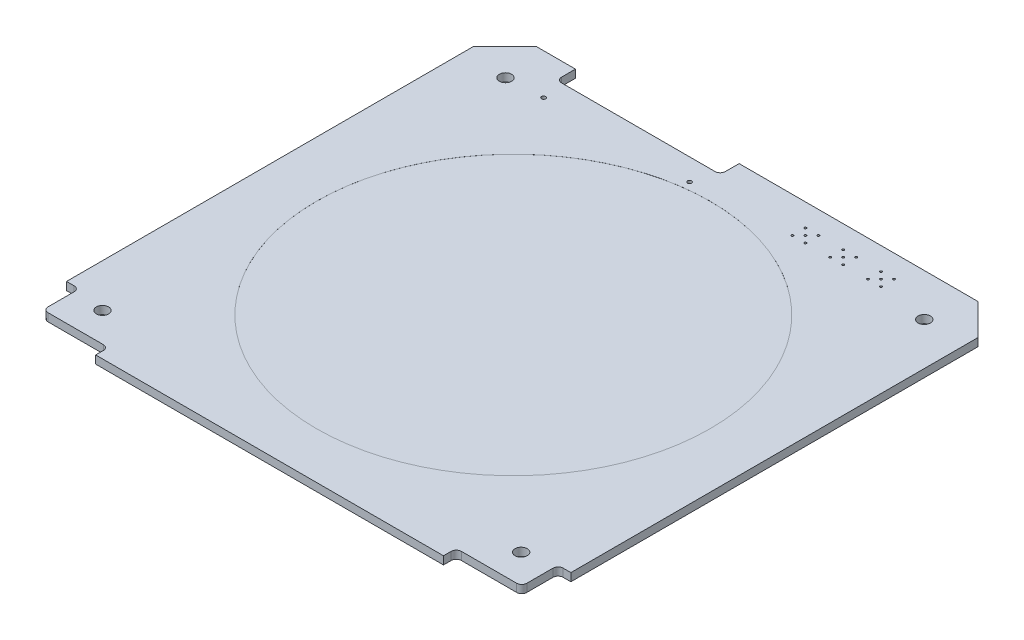
SolidWorks part; units mm, degrees
ref_plane "Front Plane" through (0, 0, 0) normal (0, 0, 1) x (1, 0, 0)
ref_plane "Top Plane" through (0, 0, 0) normal (0, 1, 0) x (1, 0, 0)
ref_plane "Right Plane" through (0, 0, 0) normal (1, 0, 0) x (0, 0, -1)
sketch "Sketch1" plane through (0, 0, 0) normal (0, 1, 0) x (1, 0, 0)
  line L0 (-49.3567, 41.6048) -> (-43.2567, 47.7048)
  line L1 (-34.0567, -47.5952) -> (33.9433, -47.5952)
  line L2 (-49.3567, -37.9952) -> (-49.3567, 41.6048)
  line L3 (-43.2567, 47.7048) -> (-35.5567, 47.7048)
  line L4 (49.2433, -37.9952) -> (49.2433, 41.6048)
  line L5 (-49.3567, -47.5952) -> (49.2979, 47.5386) construction
  line L6 (-49.3567, 47.7048) -> (49.2433, -47.5952) construction
  line L7 (-0.0567, 0.0548) -> (-0.0567, 47.7048) construction
  line L8 (49.2433, 41.6048) -> (43.1433, 47.7048)
  line L9 (-46.8567, -44.0952) -> (-46.8567, -38.9952)
  line L10 (-45.8567, -45.0952) -> (-35.0567, -45.0952)
  line L11 (46.7433, -44.0952) -> (46.7433, -38.9952)
  line L12 (-49.3567, -37.9952) -> (-47.8567, -37.9952)
  line L13 (-34.0567, -47.5952) -> (-34.0567, -46.0952)
  line L14 (33.9433, -47.5952) -> (33.9433, -46.0952)
  line L15 (49.2433, -37.9952) -> (47.7433, -37.9952)
  line L16 (34.9433, -45.0952) -> (45.7433, -45.0952)
  line L17 (-46.8567, -45.0952) -> (-46.8567, 41.6048) construction
  line L18 (46.7433, -45.0952) -> (46.7433, 41.6048) construction
  line L19 (-34.5567, 44.0048) -> (-4.5567, 44.0048)
  line L20 (-46.8567, -45.0952) -> (46.7433, -45.0952) construction
  line L21 (-49.3567, -47.5952) -> (49.2433, -47.5952) construction
  line L22 (-49.3567, -47.5952) -> (-49.3567, 41.6048) construction
  line L23 (49.2433, -47.5952) -> (49.2433, 41.6048) construction
  line L24 (-35.5567, 47.7048) -> (-35.5567, 45.0048)
  line L25 (-3.5567, 47.7048) -> (-3.5567, 45.0048)
  line L26 (-3.5567, 47.7048) -> (43.1433, 47.7048)
  line L27 (-43.2567, 44.0048) -> (43.1433, 44.0048) construction
  line L28 (21.2133, 40.7348) -> (23.7533, 40.7348) construction
  line L29 (-43.2567, 47.7048) -> (43.1433, 47.7048) construction
  line L30 (28.6133, 40.7348) -> (31.1533, 40.7348) construction
  line L31 (28.6133, 40.7348) -> (28.6133, 43.2748) construction
  line L32 (28.6133, 43.2748) -> (31.1533, 43.2748) construction
  line L33 (31.1533, 40.7348) -> (31.1533, 43.2748) construction
  line L34 (28.6133, 40.7348) -> (31.1533, 43.2748) construction
  line L35 (28.6133, 43.2748) -> (31.1533, 40.7348) construction
  line L36 (21.2133, 40.7348) -> (21.2133, 43.2748) construction
  line L37 (21.2133, 43.2748) -> (23.7533, 43.2748) construction
  line L38 (23.7533, 40.7348) -> (23.7533, 43.2748) construction
  line L39 (21.2133, 40.7348) -> (23.7533, 43.2748) construction
  line L40 (21.2133, 43.2748) -> (23.7533, 40.7348) construction
  line L41 (13.8133, 40.7348) -> (16.3533, 40.7348) construction
  line L42 (13.8133, 40.7348) -> (13.8133, 43.2748) construction
  line L43 (13.8133, 43.2748) -> (16.3533, 43.2748) construction
  line L44 (16.3533, 40.7348) -> (16.3533, 43.2748) construction
  line L45 (13.8133, 40.7348) -> (16.3533, 43.2748) construction
  line L46 (13.8133, 43.2748) -> (16.3533, 40.7348) construction
  arc A0 (47.7433, -37.9952) -> (46.7433, -38.9952) centre (47.7433, -38.9952) ccw
  arc A1 (34.9433, -45.0952) -> (33.9433, -46.0952) centre (34.9433, -46.0952) ccw
  arc A2 (-34.0567, -46.0952) -> (-35.0567, -45.0952) centre (-35.0567, -46.0952) ccw
  arc A3 (-46.8567, -38.9952) -> (-47.8567, -37.9952) centre (-47.8567, -38.9952) ccw
  arc A4 (46.7433, -44.0952) -> (45.7433, -45.0952) centre (45.7433, -44.0952) cw
  arc A5 (-45.8567, -45.0952) -> (-46.8567, -44.0952) centre (-45.8567, -44.0952) cw
  arc A6 (-4.5567, 44.0048) -> (-3.5567, 45.0048) centre (-4.5567, 45.0048) ccw
  arc A7 (-34.5567, 44.0048) -> (-35.5567, 45.0048) centre (-34.5567, 45.0048) cw
  circle A8 centre (-33.8267, 39.7448) radius 0.4
  circle A9 centre (-5.2767, 39.7448) radius 0.4
  circle A10 centre (29.8833, 42.0048) radius 0.2125
  circle A11 centre (28.6133, 43.2748) radius 0.2125
  circle A12 centre (31.1533, 43.2748) radius 0.2125
  circle A13 centre (31.1533, 40.7348) radius 0.2125
  circle A14 centre (28.6133, 40.7348) radius 0.2125
  circle A15 centre (22.4833, 42.0048) radius 0.2125
  circle A16 centre (21.2133, 43.2748) radius 0.2125
  circle A17 centre (23.7533, 43.2748) radius 0.2125
  circle A18 centre (23.7533, 40.7348) radius 0.2125
  circle A19 centre (21.2133, 40.7348) radius 0.2125
  circle A20 centre (15.0833, 42.0048) radius 0.2125
  circle A21 centre (13.8133, 43.2748) radius 0.2125
  circle A22 centre (16.3533, 43.2748) radius 0.2125
  circle A23 centre (16.3533, 40.7348) radius 0.2125
  circle A24 centre (13.8133, 40.7348) radius 0.2125
  point P0 (0, 0)
  point P26 (46.7433, -37.9952)
  point P29 (33.9433, -45.0952)
  point P32 (-34.0567, -45.0952)
  point P35 (-46.8567, -37.9952)
  dimension "D9" = 1
  dimension "D10" = 1
  dimension "D11" = 3.7
  dimension "D14" = 1
  dimension "D16" = 0.8
  dimension "D18" = 7.96
  dimension "D19" = 9.43
  dimension "D20" = 28.55
  dimension "D21" = 0.425
  dimension "D22" = 1.27
  dimension "D1" = 47.7048
  dimension "D2" = 98.6
  dimension "D3" = 6.1
  dimension "D4" = 6.1
  dimension "D5" = 95.3
  dimension "D6" = 2.5
  dimension "D7" = 85.7
  dimension "D8" = 15.3
  dimension "D12" = 13.8
  dimension "D13" = 32
  dimension "D15" = 137.1279
  dimension "D17" = 7.96
  dimension "D23" = 5.7
  dimension "D24" = 13.26
  dimension "D25" = 1.27
  dimension "D27" = 5.7
  dimension "D28" = 7.4
  dimension "D26" = 3
extrude "Boss-Extrude1" add sketch "Sketch1" along normal blind 1.56
sketch "Sketch2" plane through (0, 1.56, 0) normal (0, 1, 0) x (1, 0, 0)
  circle A0 centre (0, 0) radius 38.5
  dimension "D1" = 77
extrude "Cut-Extrude1" cut sketch "Sketch2" against normal blind 0.01
sketch "Sketch7" plane through (0, 1.56, 0) normal (0, 1, 0) x (1, 0, 0)
  line L1 (-46.75, -45) -> (46.75, -45)
  line L2 (-46.75, -45) -> (-46.75, 45)
  line L3 (-46.75, 45) -> (46.75, 45)
  line L4 (46.75, -45) -> (46.75, 45)
  line L5 (-46.75, -45) -> (46.75, 45)
  line L6 (-46.75, 45) -> (46.75, -45)
  point P0 (0, 0)
  dimension "D1" = 90
  dimension "D2" = 93.5
hole_wizard "M2 Clearance Hole2" positions "Sketch9" profile "Sketch8" hole size "M2" standard "ANSI Metric"
sketch "Sketch9" plane through (0, 1.56, 0) normal (0, 1, 0) x (1, 0, 0)
  line L0 (-46.75, -45) -> (46.75, 45) construction
  line L1 (-46.75, 45) -> (46.75, -45) construction
  point P0 (-40.9295, 39.3974)
  point P2 (40.9295, 39.3974)
  point P4 (40.9295, -39.3974)
  point P6 (-40.9295, -39.3974)
  dimension "D1" = 56.81
  dimension "D2" = 56.81
  dimension "D3" = 56.81
  dimension "D4" = 56.81
sketch "Sketch8" plane through (-40.9295, 1.56, -39.3974) normal (1, 0, 0) x (0, 0, 1)
  line L0 (0, 0) -> (0, 38.821)
  line L1 (0, 38.821) -> (1.2, 38.1)
  line L2 (1.2, 38.1) -> (1.2, 0)
  line L5 (1.2, 0) -> (0, 0)
  line L10 (0, 38.821) -> (-1.2, 38.1) construction
  line L11 (0, -6.35) -> (0, 107.95) construction
  dimension "Hole Dia." = 2.4
  dimension "Hole Depth" = 38.1
  dimension "Drill Angle" = 118
